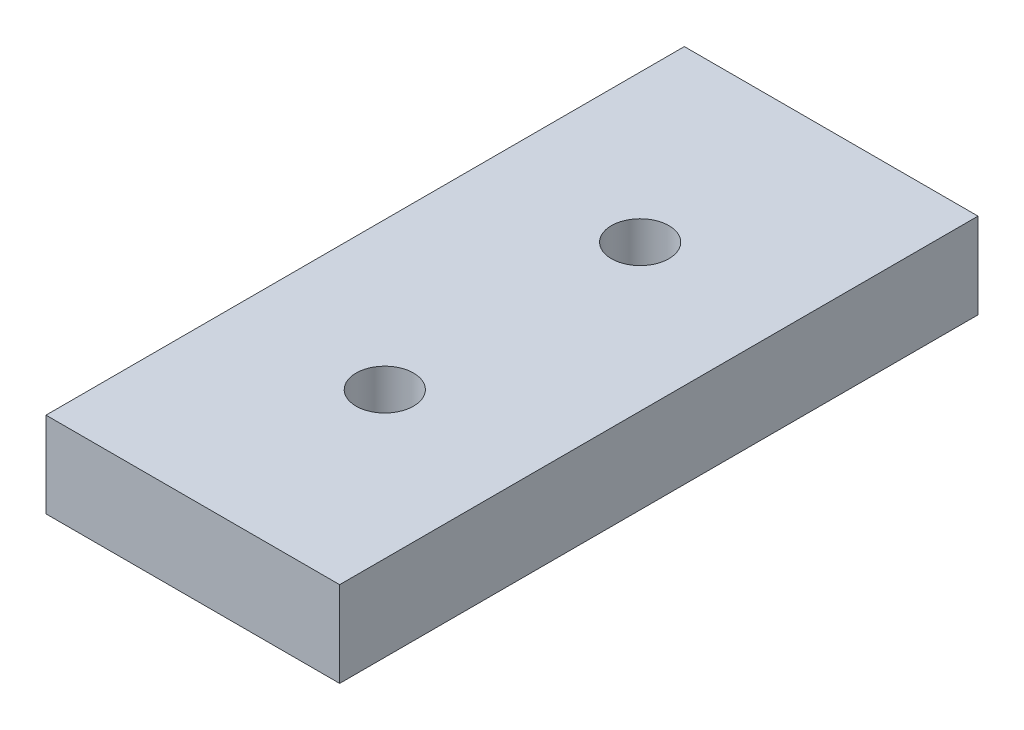
SolidWorks part; units mm, degrees
ref_plane "Front Plane" through (0, 0, 0) normal (0, 0, 1) x (1, 0, 0)
ref_plane "Top Plane" through (0, 0, 0) normal (0, 1, 0) x (1, 0, 0)
ref_plane "Right Plane" through (0, 0, 0) normal (1, 0, 0) x (0, 0, -1)
sketch "Sketch1" plane through (0, 0, 0) normal (0, 1, 0) x (1, 0, 0)
  line L0 (11.5374, 15) -> (11.5374, 35) construction
  line L1 (0, 0) -> (23, 0)
  line L2 (0, 0) -> (0, 50)
  line L3 (0, 50) -> (23, 50)
  line L4 (23, 0) -> (23, 50)
  line L5 (0, 25) -> (11.5374, 25) construction
  circle A0 centre (11.5374, 35) radius 2.25
  circle A1 centre (11.5374, 15) radius 2.25
  dimension "D3" = 4.5
  dimension "D4" = 20
  dimension "D1" = 50
  dimension "D2" = 23
extrude "Boss-Extrude1" add sketch "Sketch1" along normal blind 6.7
